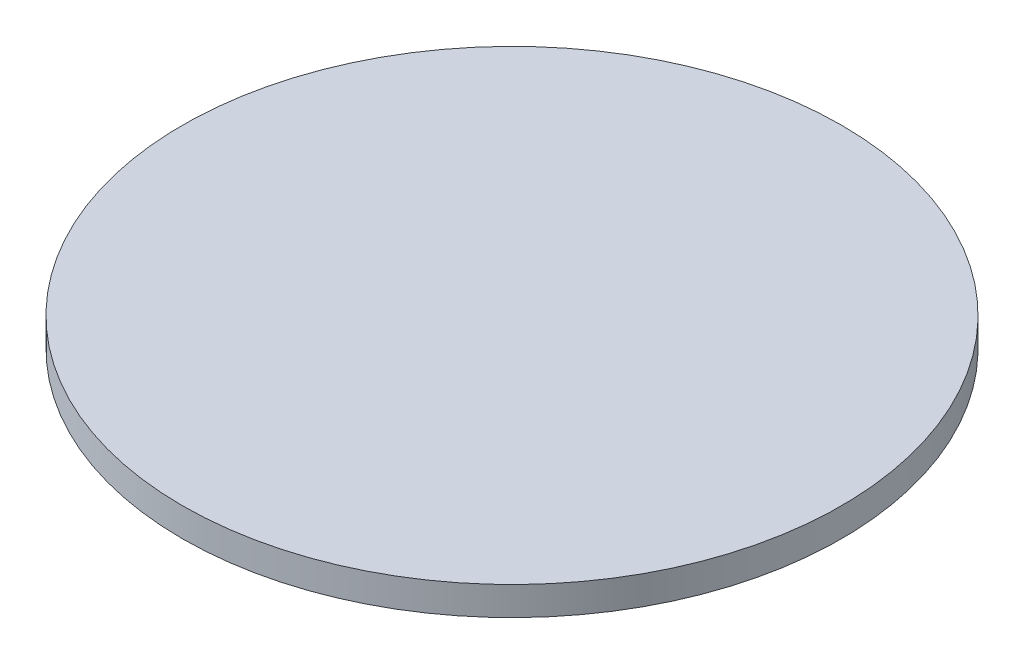
SolidWorks part; units mm, degrees
ref_plane "Front Plane" through (0, 0, 0) normal (0, 0, 1) x (1, 0, 0)
ref_plane "Top Plane" through (0, 0, 0) normal (0, 1, 0) x (1, 0, 0)
ref_plane "Right Plane" through (0, 0, 0) normal (1, 0, 0) x (0, 0, -1)
sketch "Sketch1" plane through (0, 0, 0) normal (0, 1, 0) x (1, 0, 0)
  circle A0 centre (0, 0) radius 11.5
  dimension "D1" = 23
extrude "Boss-Extrude1" add sketch "Sketch1" along normal blind 1
